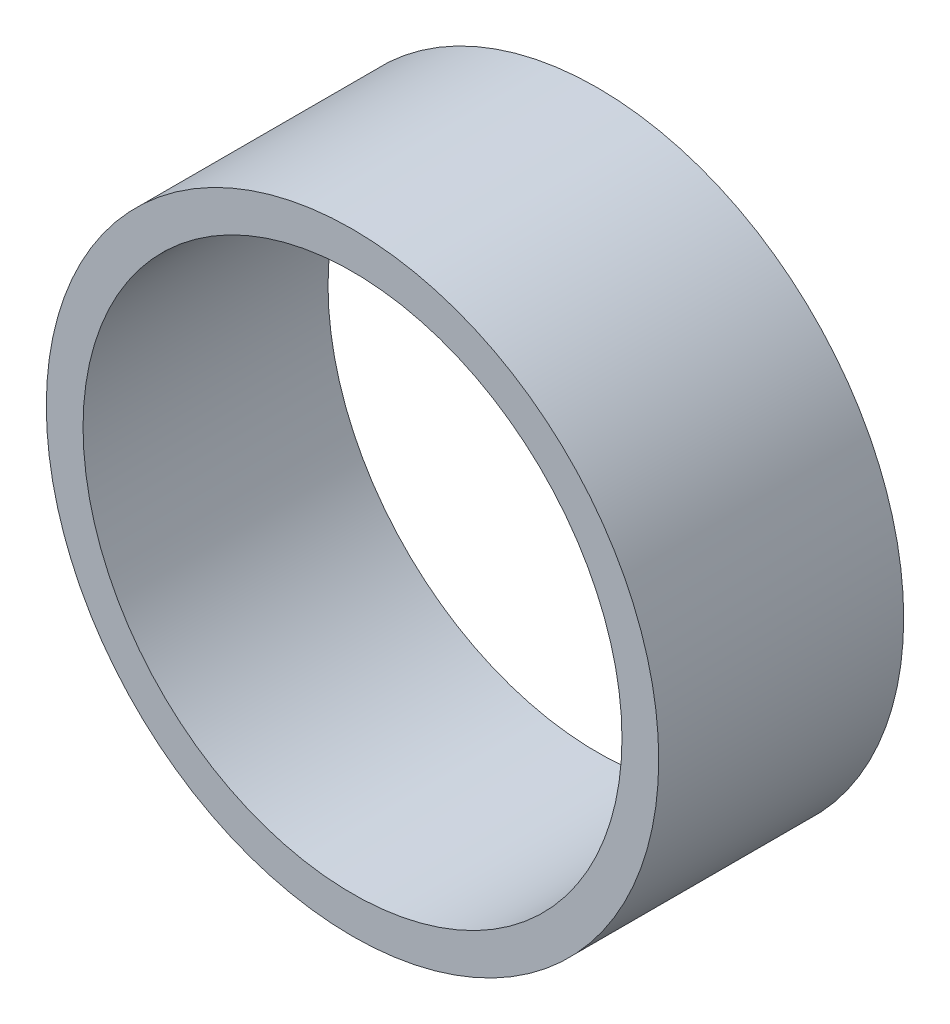
SolidWorks part; units mm, degrees
ref_plane "Plan de face" through (0, 0, 0) normal (0, 0, 1) x (1, 0, 0)
ref_plane "Plan de dessus" through (0, 0, 0) normal (0, 1, 0) x (1, 0, 0)
ref_plane "Plan de droite" through (0, 0, 0) normal (1, 0, 0) x (0, 0, -1)
sketch "Esquisse1" plane through (0, 0, 0) normal (0, 0, 1) x (1, 0, 0)
  circle A0 centre (0, 0) radius 25
extrude "Boss.-Extru.1" add sketch "Esquisse1" along normal blind 20
sketch "Esquisse2" plane through (0, 0, 20) normal (0, 0, 1) x (1, 0, 0)
  circle A0 centre (0, 0) radius 22
extrude "Enlèv. mat.-Extru.1" cut sketch "Esquisse2" against normal through all
